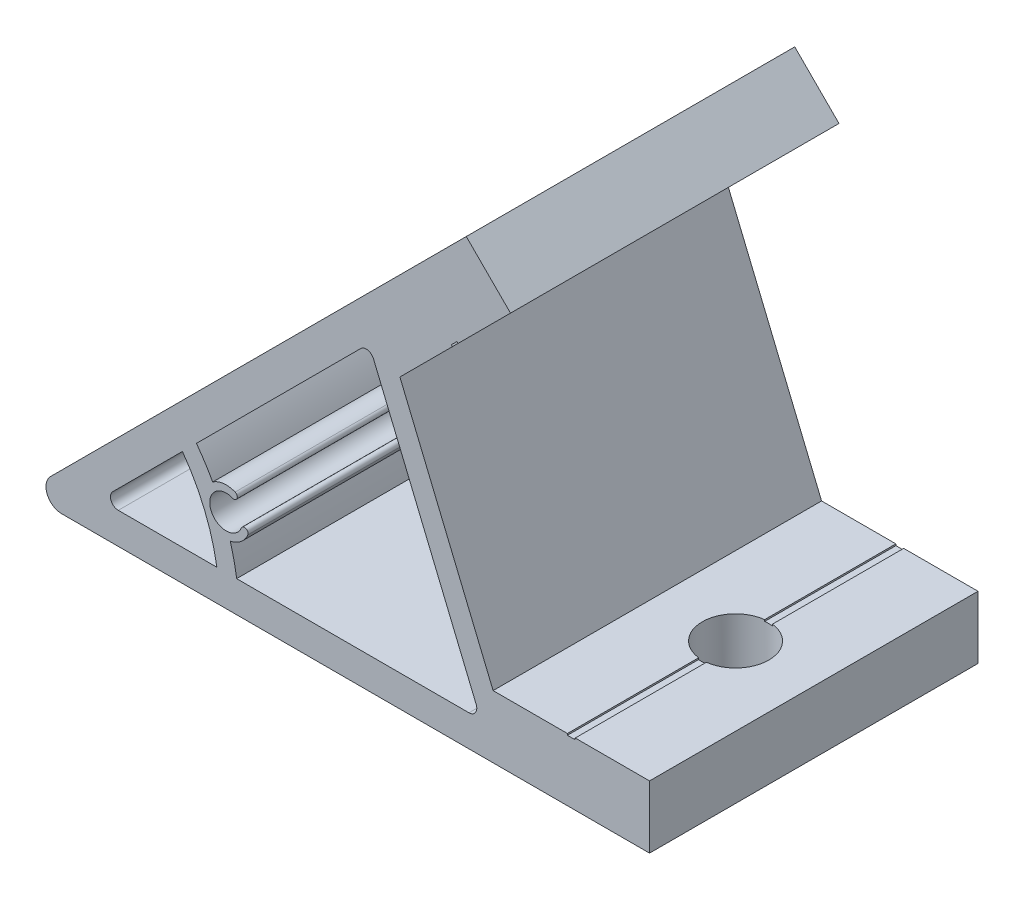
SolidWorks part; units mm, degrees
material "1060 合金"
ref_plane "前视基准面" through (0, 0, 0) normal (0, 0, 1) x (1, 0, 0)
ref_plane "上视基准面" through (0, 0, 0) normal (0, 1, 0) x (1, 0, 0)
ref_plane "右视基准面" through (0, 0, 0) normal (1, 0, 0) x (0, 0, -1)
sketch "草图1" plane through (0, 0, 0) normal (0, 0, 1) x (1, 0, 0)
  line L0 (0, 0) -> (60, 0)
  line L1 (60, 0) -> (60, 8)
  line L2 (60, 8) -> (40, 8)
  line L3 (40, 8) -> (28.0833, 36.7696)
  line L4 (28.0833, 36.7696) -> (42.2254, 50.9117)
  line L5 (42.2254, 50.9117) -> (36.5685, 56.5685)
  line L6 (36.5685, 56.5685) -> (-20, 0)
  line L7 (-20, 0) -> (0, 0)
  line L8 (24.1303, 38.4735) -> (2.0671, 16.4102)
  line L9 (-10.3431, 4) -> (4.6779, 4)
  line L10 (38.4097, 4) -> (24.1303, 38.4735)
  line L11 (-20, 0) -> (17.8242, 15.6673) construction
  line L12 (6.8404, 13.0727) -> (7.0126, 12.657) construction
  line L13 (8.0506, 10.151) -> (8.2228, 9.7352) construction
  line L14 (0.2784, 14.6215) -> (-10.3431, 4)
  line L15 (7.2075, 4) -> (38.4097, 4)
  arc A0 (4.6779, 4) -> (0.2784, 14.6215) centre (-20, 0) ccw
  arc A1 (7.2075, 4) -> (6.3826, 7.7595) centre (-20, 0) ccw
  arc A3 (7.0119, 13.4888) -> (4.1421, 13.1685) centre (5.8686, 10.7151) ccw
  arc A4 (6.6689, 12.6567) -> (7.8074, 9.9081) centre (5.8686, 10.7151) ccw
  arc A5 (6.6689, 12.6567) -> (7.0119, 13.4888) centre (6.8404, 13.0727) ccw
  arc A7 (8.6383, 9.5623) -> (7.8074, 9.9081) centre (8.2228, 9.7352) ccw
  arc A8 (4.1421, 13.1685) -> (2.0671, 16.4102) centre (-20, 0) ccw
  arc A9 (6.3826, 7.7595) -> (8.6383, 9.5623) centre (5.8686, 10.7151) ccw
  point P20 (8.0524, 9.6607)
  dimension "D12" = 50
  dimension "D13" = 55
  dimension "D14" = 6
  dimension "D16" = 4.2
  dimension "D1" = 80
  dimension "D2" = 80
  dimension "D3" = 45
  dimension "D4" = 8
  dimension "D5" = 8
  dimension "D6" = 20
  dimension "D7" = 20
  dimension "D8" = 20
  dimension "D9" = 3
  dimension "D10" = 4
  dimension "D11" = 4
  dimension "D15" = 28
  dimension "D17" = 29.8
extrude "凸台-拉伸1" add sketch "草图1" along normal blind 42
fillet "圆角1" radius 2 1 edges at (-20, 0, 21)
fillet "圆角2" radius 1 1 edges at (-10.3431, 4, 21)
fillet "圆角3" radius 1 2 edges at (38.4097, 4, 21) (24.1303, 38.4735, 21)
sketch "草图2" plane through (0, 8, 0) normal (0, 1, 0) x (1, 0, 0)
  line L0 (60, -42) -> (60, 0) construction
  line L1 (60, -42) -> (40, -42) construction
  circle A0 centre (50, -21) radius 4.25
  dimension "D3" = 8.5
  dimension "D1" = 10
  dimension "D2" = 21
extrude "切除-拉伸1" cut sketch "草图2" against normal up to next
sketch "草图3" plane through (-4.3431, 4.3431, 0) normal (0.7071, -0.7071, 0) x (0, 0, -1)
  line L0 (0, 45.8579) -> (0, 65.8579) construction
  line L1 (-42, 65.8579) -> (0, 65.8579) construction
  circle A0 centre (-21, 55.8579) radius 4.25
  dimension "D1" = 8.5
  dimension "D2" = 21
  dimension "D3" = 10
extrude "切除-拉伸2" cut sketch "草图3" against normal up to next
sketch "草图4" plane through (-4.3431, 4.3431, 0) normal (0.7071, -0.7071, 0) x (0, 0, -1)
  line L0 (0, 45.8579) -> (0, 65.8579) construction
  line L1 (0, 55.3579) -> (-42, 55.3579)
  line L2 (0, 55.3579) -> (0, 56.3579)
  line L3 (0, 56.3579) -> (-42, 56.3579)
  line L4 (-42, 55.3579) -> (-42, 56.3579)
  line L5 (-42, 45.8579) -> (-42, 65.8579) construction
  line L6 (0, 55.8579) -> (-42, 55.8579) construction
  point P10 (0, 0)
  point P11 (0, 0)
  point P12 (0, 0)
  point P13 (0, 55.8579)
  dimension "D1" = 0.5
extrude "切除-拉伸3" cut sketch "草图4" against normal blind 0.2
sketch "草图5" plane through (0, 8, 0) normal (0, 1, 0) x (1, 0, 0)
  line L0 (60, -42) -> (40, -42) construction
  line L1 (49.5, -42) -> (50.5, -42)
  line L2 (49.5, -42) -> (49.5, 0)
  line L3 (49.5, 0) -> (50.5, 0)
  line L4 (50.5, -42) -> (50.5, 0)
  line L5 (60, 0) -> (40, 0) construction
  line L6 (50, -42) -> (50, 0) construction
  point P10 (0, 0)
  point P13 (0, 0)
  point P14 (50, -42)
  dimension "D1" = 0.5
extrude "切除-拉伸4" cut sketch "草图5" against normal blind 0.2
